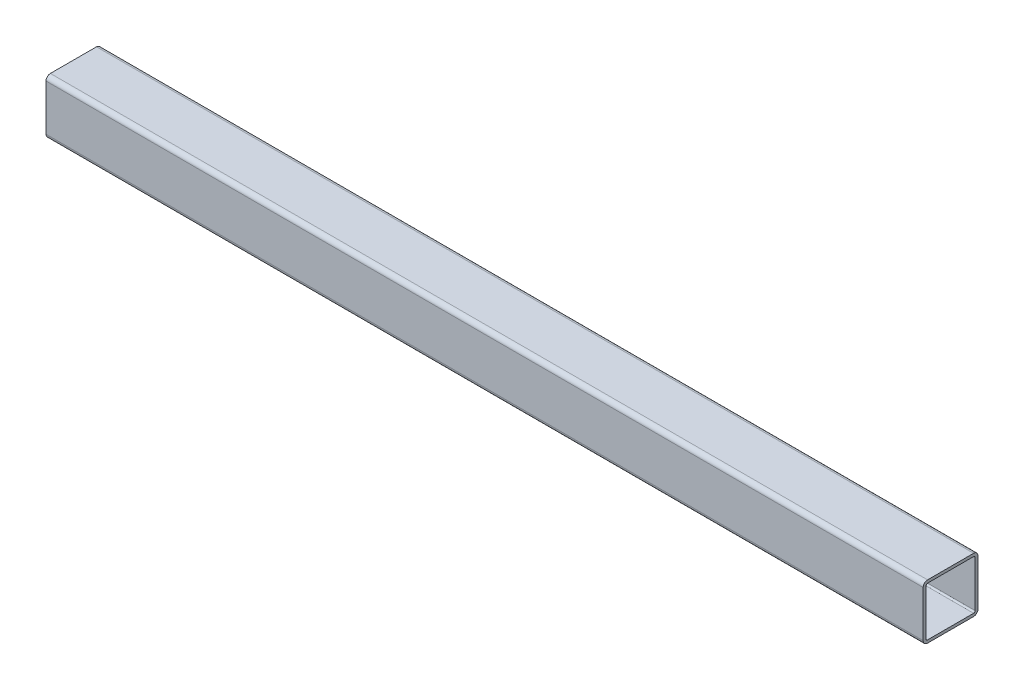
SolidWorks part; units mm, degrees
material "Plain Carbon Steel"
ref_plane "Front Plane" through (0, 0, 0) normal (0, 0, 1) x (1, 0, 0)
ref_plane "Top Plane" through (0, 0, 0) normal (0, 1, 0) x (1, 0, 0)
ref_plane "Right Plane" through (0, 0, 0) normal (1, 0, 0) x (0, 0, -1)
sketch "Sketch1" plane through (0, 0, 0) normal (1, 0, 0) x (0, 0, -1)
  line L0 (0, 2.54) -> (0, 29.21)
  line L1 (-2.54, 31.75) -> (-29.21, 31.75)
  line L2 (-31.75, 29.21) -> (-31.75, 2.54)
  line L3 (-29.21, 0) -> (-2.54, 0)
  line L4 (-1.651, 2.54) -> (-1.651, 29.21)
  line L5 (-2.54, 30.099) -> (-29.21, 30.099)
  line L6 (-30.099, 29.21) -> (-30.099, 2.54)
  line L7 (-29.21, 1.651) -> (-2.54, 1.651)
  arc A0 (-31.75, 2.54) -> (-29.21, 0) centre (-29.21, 2.54) ccw
  arc A1 (0, 2.54) -> (-2.54, 0) centre (-2.54, 2.54) cw
  arc A2 (0, 29.21) -> (-2.54, 31.75) centre (-2.54, 29.21) ccw
  arc A3 (-31.75, 29.21) -> (-29.21, 31.75) centre (-29.21, 29.21) cw
  arc A4 (-1.651, 29.21) -> (-2.54, 30.099) centre (-2.54, 29.21) ccw
  arc A5 (-30.099, 29.21) -> (-29.21, 30.099) centre (-29.21, 29.21) cw
  arc A6 (-30.099, 2.54) -> (-29.21, 1.651) centre (-29.21, 2.54) ccw
  arc A7 (-1.651, 2.54) -> (-2.54, 1.651) centre (-2.54, 2.54) cw
  point P12 (0, 0)
  point P15 (0, 31.75)
  point P18 (-31.75, 31.75)
  dimension "D3" = 2.54
  dimension "D1" = 31.75
  dimension "D2" = 31.75
  dimension "D4" = 1.651
extrude "Boss-Extrude1" add sketch "Sketch1" along normal blind 203.2
scale "Scale1" scale about centroid uniform scaling no x scale factor 1 y scale factor 0.4 z scale factor 0.4
